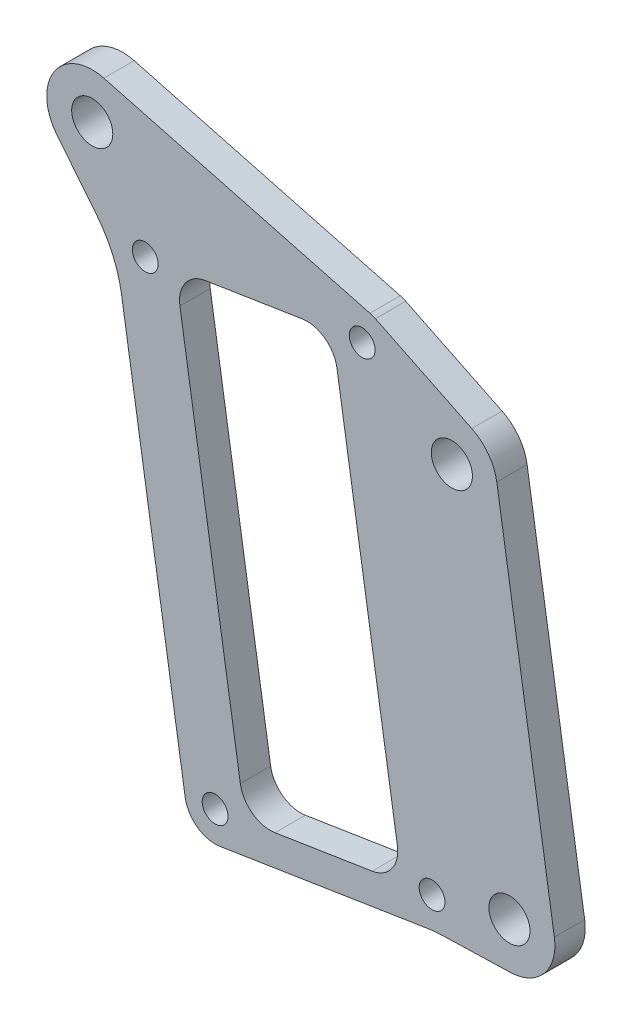
SolidWorks part; units mm, degrees
material "ABS PC"
ref_plane "Front Plane" through (0, 0, 0) normal (0, 0, 1) x (1, 0, 0)
ref_plane "Top Plane" through (0, 0, 0) normal (0, 1, 0) x (1, 0, 0)
ref_plane "Right Plane" through (0, 0, 0) normal (1, 0, 0) x (0, 0, -1)
sketch "Sketch1" plane through (0, 0, 0) normal (0, 0, 1) x (1, 0, 0)
  line L0 (-3.7107, -2.9853) -> (3.0775, -11.4229)
  line L1 (2.4151, -9.927) -> (9.7328, -56.3539)
  line L2 (1.2203, 4.6035) -> (29.0844, -2.7827)
  line L3 (29.661, -2.9972) -> (39.7487, -7.9099)
  line L4 (42.3679, -11.4501) -> (48.3988, -49.7127)
  line L5 (35.681, -55.4522) -> (43.8331, -55.2147)
  line L6 (13.3634, -58.9958) -> (36.0829, -55.4148)
  line L7 (5.5513, -9.4327) -> (35.5886, -52.2785) construction
  line L8 (20.57, -30.8556) -> (15.581, 0.7968) construction
  line L9 (32.4523, -52.7729) -> (25.1346, -6.346)
  line L10 (32.4523, -52.7729) -> (16.0054, -55.3652)
  line L11 (25.1346, -6.346) -> (8.6876, -8.9384)
  line L12 (16.0054, -55.3652) -> (8.6876, -8.9384)
  line L13 (32.4523, -52.7729) -> (8.6876, -8.9384) construction
  line L14 (25.1346, -6.346) -> (16.0054, -55.3652) construction
  circle A0 centre (37.6635, -12.1916) radius 4.7625
  circle A1 centre (43.6944, -50.4542) radius 4.7625
  circle A2 centre (37.6635, -12.1916) radius 2.15 construction
  circle A3 centre (43.6944, -50.4542) radius 2.15 construction
  circle A4 centre (0, 0) radius 4.7625
  circle A5 centre (0, 0) radius 2.15 construction
  circle A6 centre (35.5886, -52.2785) radius 3.175
  circle A7 centre (12.8691, -55.8595) radius 3.175
  circle A8 centre (5.5513, -9.4327) radius 3.175
  circle A9 centre (28.2709, -5.8517) radius 3.175
  dimension "D1" = 9.525
  dimension "D2" = 6.35
  dimension "D3" = 3.175
extrude "Boss-Extrude1" add sketch "Sketch1" along normal blind 3.175 contours A9 | A9 L2 A4 L0 L1 A8 L11 | A4 | A8 | A8 L0 L1 A7 L12 | A7 | A7 L6 L5 A6 L10 | A1 A6 | A6 L6 L5 A1 | A6 A1 | A1 A6 | A6 L5 L6 | A9 L9 A6 A1 L4 A0 L3 | A0 | A8 L1 L0
fillet "Fillet1" radius 3.175 4 edges at (32.4523, -52.7729, 1.5875) (25.1346, -6.346, 1.5875) (16.0054, -55.3652, 1.5875) (8.6876, -8.9384, 1.5875)
fillet "Fillet2" radius 12.7 2 edges at (35.8832, -55.4463, 1.5875) (2.5469, -10.7633, 1.5875)
hole_wizard "#2 Clearance Hole1" positions "Sketch2" profile "Sketch3" hole size "#2" standard "ANSI Inch" end condition through all
sketch "Sketch2" plane through (0, 0, 3.175) normal (0, 0, 1) x (1, 0, 0)
  line L0 (5.5513, -9.4327) -> (35.5886, -52.2785) construction
  point P0 (5.5513, -9.4327)
  point P4 (28.2709, -5.8517)
  point P7 (35.5886, -52.2785)
  point P10 (12.8691, -55.8595)
  point P14 (8.6876, -8.9384)
sketch "Sketch3" plane through (5.5513, -9.4327, 3.175) normal (1, 0, 0) x (0, -1, 0)
  line L0 (0, 0) -> (0, 3.175)
  line L1 (0, 3.175) -> (1.3525, 3.175)
  line L2 (1.3525, 3.175) -> (1.3525, 0)
  line L5 (1.3525, 0) -> (0, 0)
  line L11 (0, -6.35) -> (0, 107.95) construction
  dimension "Thru Hole Dia." = 2.7051
  dimension "Thru Hole Depth" = 3.175
hole_wizard "#6 Clearance Hole1" positions "Sketch4" profile "Sketch5" hole size "#6" standard "ANSI Inch" end condition through all
sketch "Sketch4" plane through (0, 0, 3.175) normal (0, 0, 1) x (1, 0, 0)
  point P0 (0, 0)
  point P3 (37.6635, -12.1916)
  point P6 (43.6944, -50.4542)
sketch "Sketch5" plane through (0, 0, 3.175) normal (1, 0, 0) x (0, -1, 0)
  line L0 (0, 0) -> (0, 3.175)
  line L1 (0, 3.175) -> (2.1526, 3.175)
  line L2 (2.1526, 3.175) -> (2.1526, 0)
  line L5 (2.1526, 0) -> (0, 0)
  line L11 (0, -6.35) -> (0, 107.95) construction
  dimension "Thru Hole Dia." = 4.3053
  dimension "Thru Hole Depth" = 3.175
